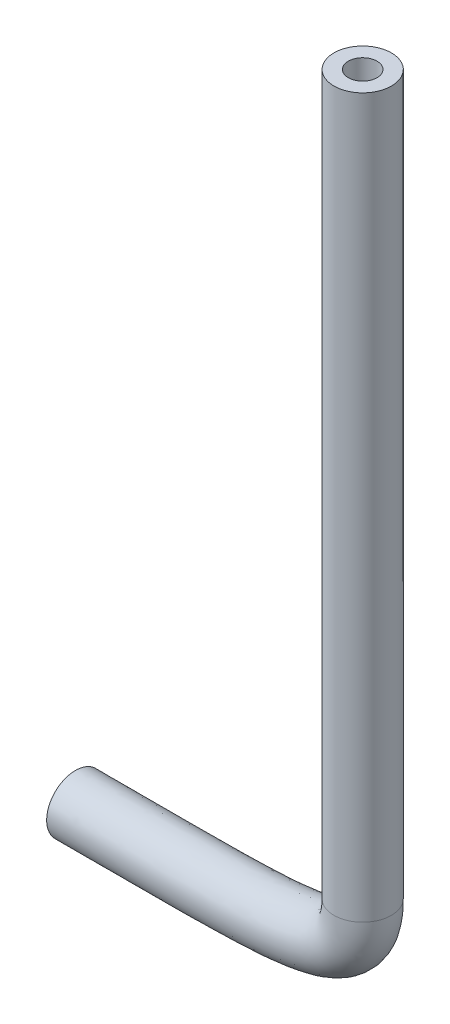
SolidWorks part; units mm, degrees
other "Pipe1"
material "PTFE (general)"
ref_plane "Front" through (0, 0, 0) normal (0, 0, 1) x (1, 0, 0)
ref_plane "Top" through (0, 0, 0) normal (0, 1, 0) x (1, 0, 0)
ref_plane "Right" through (0, 0, 0) normal (1, 0, 0) x (0, 0, -1)
sketch "PipeSke" plane through (0, 0, 0) normal (0, 0, 1) x (1, 0, 0)
  line L0 (0, 0) -> (-2, 0)
  line L1 (6, 21.7045) -> (6, 1.7045)
  spline S0 degree 3 poles (0, 0) (4.6199, 0) (6, 0.036) (6, 1.7045) knots 0 0 0 0 1 1 1 1
  dimension "D1" = 2
  dimension "D2" = 20
sketch "PipeRing" plane through (0, 0, 0) normal (1, 0, 0) x (0, 0, -1)
  circle A0 centre (0, 0) radius 0.8
  circle A1 centre (0, 0) radius 0.4
  dimension "D1" = 1.6
  dimension "D2" = 0.8
sweep "Pipe" add profiles "PipeRing" path "PipeSke"
